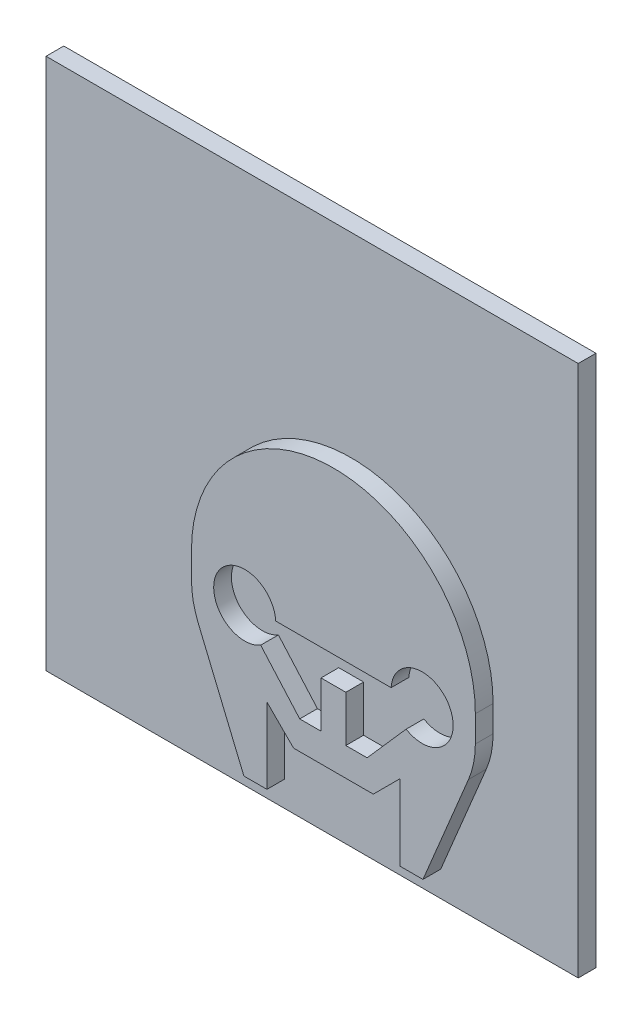
SolidWorks part; units mm, degrees
material "Obyčejná uhlíková ocel"
ref_plane "Přední rovina" through (0, 0, 0) normal (0, 0, 1) x (1, 0, 0)
ref_plane "Horní rovina" through (0, 0, 0) normal (0, 1, 0) x (1, 0, 0)
ref_plane "Pravá rovina" through (0, 0, 0) normal (1, 0, 0) x (0, 0, -1)
sketch "Skica1" plane through (0, 0, 0) normal (0, 0, 1) x (1, 0, 0)
  line L1 (0, 0) -> (300, 0)
  line L2 (0, 0) -> (0, 300)
  line L3 (0, 300) -> (300, 300)
  line L4 (300, 0) -> (300, 300)
  dimension "D1" = 300
extrude "Přidat vysunutím1" add sketch "Skica1" along normal blind 10
sketch "Skica3" plane through (0, 0, 10) normal (0, 0, 1) x (1, 0, 0)
  line L10 (134.5271, 14.3648) -> (134.5271, 57)
  line L11 (134.5271, 57) -> (149.5271, 42)
  line L12 (149.5271, 42) -> (194.4729, 42)
  line L24 (121.5271, 14.3648) -> (134.5271, 14.3648)
  line L27 (139.4714, 99) -> (204.5286, 99)
  line L34 (179, 84) -> (165, 84)
  line L35 (165, 84) -> (165, 58)
  line L36 (165, 58) -> (153, 58)
  line L37 (153, 58) -> (131, 82.9917)
  line L42 (0, 0) -> (0, 300) construction
  line L43 (0, 0) -> (300, 0) construction
  line L44 (172, 42) -> (172, -133.7925) construction
  line L47 (222.4729, 14.3648) -> (209.4729, 14.3648)
  line L48 (209.4729, 14.3648) -> (209.4729, 57)
  line L49 (209.4729, 57) -> (194.4729, 42)
  line L50 (191, 58) -> (213, 82.9917)
  line L51 (179, 58) -> (191, 58)
  line L52 (179, 84) -> (179, 58)
  line L53 (92, 110) -> (92, 95.2299)
  line L54 (95.8462, 75.9991) -> (121.5271, 14.3648)
  line L56 (252, 110) -> (252, 95.2299)
  line L58 (252, 110) -> (252, 95.2299)
  line L59 (248.1538, 75.9991) -> (222.4729, 14.3648)
  arc A100 (252, 110) -> (92, 110) centre (172, 110) ccw
  circle A101 centre (122, 98) radius 17.5
  circle A102 centre (222, 98) radius 17.5
  arc A103 (92, 95.2299) -> (95.8462, 75.9991) centre (142, 95.2299) ccw
  arc A104 (252, 95.2299) -> (248.1538, 75.9991) centre (202, 95.2299) cw
  point P11 (172, 99)
  point P15 (92, 91.0796)
  point P29 (172, 42)
  point P41 (252, 95.2299)
  dimension "D1" = 172
  dimension "D2" = 160
  dimension "D3" = 110
  dimension "D12" = 15
  dimension "D18" = 50
  dimension "D5" = 50
  dimension "D9" = 13
  dimension "D4" = 50
  dimension "D6" = 35
  dimension "D7" = 98
  dimension "D8" = 1
  dimension "D10" = 45
  dimension "D11" = 42
  dimension "D13" = 15
  dimension "D14" = 7
  dimension "D15" = 41
  dimension "D16" = 12
  dimension "D17" = 22
extrude "Přidat vysunutím3" add sketch "Skica3" along normal blind 10
